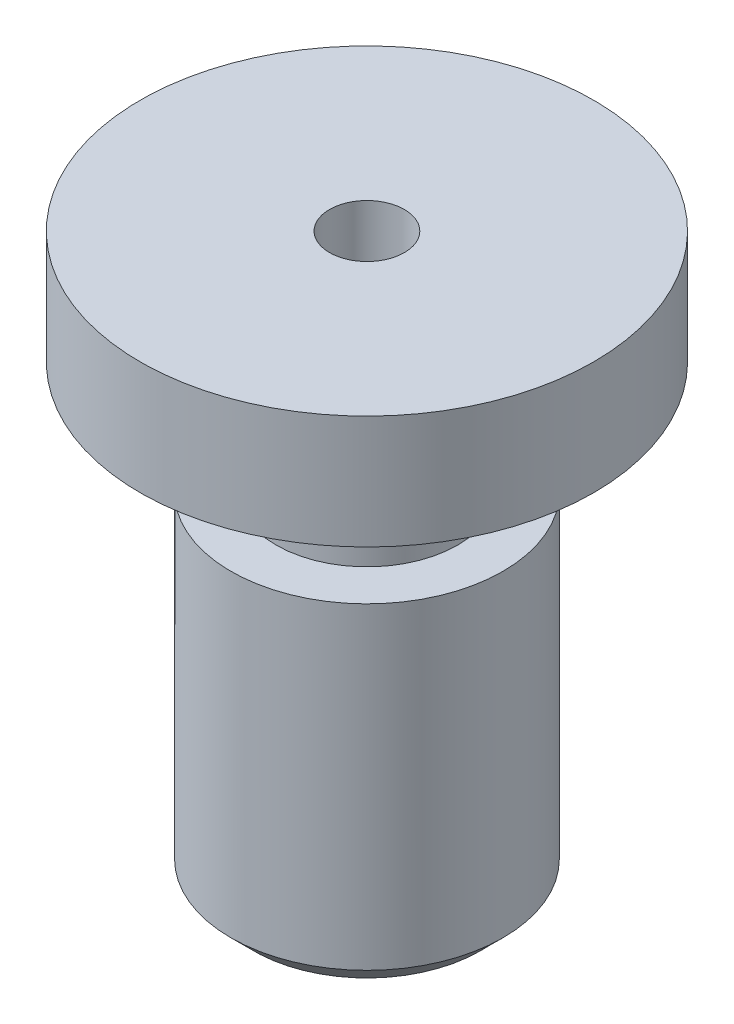
SolidWorks part; units mm, degrees
ref_plane "前视基准面" through (0, 0, 0) normal (0, 0, 1) x (1, 0, 0)
ref_plane "上视基准面" through (0, 0, 0) normal (0, 1, 0) x (1, 0, 0)
ref_plane "右视基准面" through (0, 0, 0) normal (1, 0, 0) x (0, 0, -1)
other "Configuration Table"
sketch "草图1" plane through (0, 0, 0) normal (0, 0, 1) x (1, 0, 0)
  line L0 (0, -198.1301) -> (0, 9708.3741) construction
  line L1 (0, 0) -> (-6, 0)
  line L2 (-6, 0) -> (-6, 15)
  line L3 (-6, 15) -> (-4, 15)
  line L4 (-4, 15) -> (-4, 20)
  line L5 (-4, 20) -> (-10, 20)
  line L6 (-10, 20) -> (-10, 25)
  line L7 (-10, 25) -> (0, 25)
  line L8 (0, 0) -> (0, 25)
  dimension "D1" = 12
  dimension "D2" = 2
  dimension "D3" = 5
  dimension "D4" = 15
  dimension "D5" = 20
  dimension "D6" = 5
revolve "旋转1" add sketch "草图1" angle 360 about L0
cosmetic thread "装饰螺纹线1" parameters "D2"=11
chamfer "倒角1" distance 1 angle 45 1 edges at (6, 0, 0)
sketch "草图3" plane through (0, 25, 0) normal (0, 1, 0) x (1, 0, 0)
  point P0 (0, 0)
hole_wizard "M4 螺纹孔1" positions "草图3" profile "草图4" tap size "M4" standard "GB"
sketch "草图4" plane through (0, 25, 0) normal (1, 0, 0) x (0, 0, 1)
  line L0 (0, 0) -> (0, 10.9914)
  line L1 (0, 10.9914) -> (1.65, 10)
  line L2 (1.65, 10) -> (1.65, 0)
  line L5 (1.65, 0) -> (0, 0)
  line L10 (0, 10.9914) -> (-1.65, 10) construction
  line L11 (0, -6.35) -> (0, 107.95) construction
  dimension "螺纹孔钻头直径" = 3.3
  dimension "螺纹孔钻头深度" = 10
  dimension "导头角度" = 118
cosmetic thread "孔螺蚊线1" parameters "D1"=8, "D2"=4
